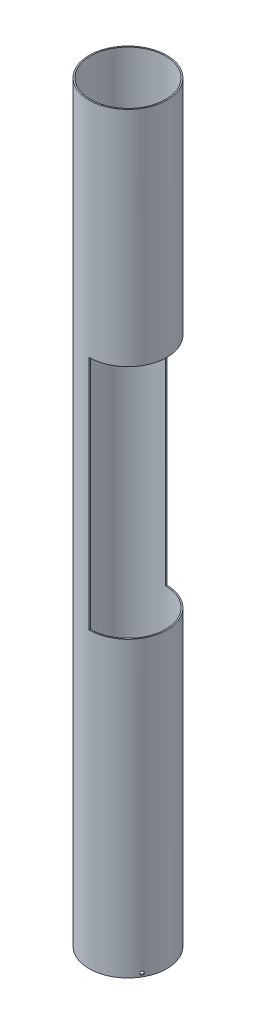
SolidWorks part; units mm, degrees
ref_plane "Front Plane" through (0, 0, 0) normal (0, 0, 1) x (1, 0, 0)
ref_plane "Top Plane" through (0, 0, 0) normal (0, 1, 0) x (1, 0, 0)
ref_plane "Right Plane" through (0, 0, 0) normal (1, 0, 0) x (0, 0, -1)
sketch "Sketch1" plane through (0, 0, 0) normal (0, 1, 0) x (1, 0, 0)
  circle A0 centre (0, 0) radius 38.1
  circle A3 centre (0, 0) radius 39.37
extrude "Boss-Extrude1" add sketch "Sketch1" along normal blind 762
sketch "Sketch2" plane through (0, 0, 0) normal (0, 0, 1) x (1, 0, 0)
  circle A0 centre (0, 3.2871) radius 1.6929
extrude "Cut-Extrude1" cut sketch "Sketch2" against normal blind 61.4
pattern_circular "CirPattern3" count 3 over 360 of "Cut-Extrude1"
sketch "Sketch3" plane through (0, 0, 0) normal (1, 0, 0) x (0, 0, -1)
  line L0 (-39.37, 665.4) -> (-39.37, 0) construction
  line L1 (-39.37, 513.9904) -> (39.37, 513.9904)
  line L2 (-39.37, 513.9904) -> (-39.37, 282.655)
  line L4 (39.37, 513.9904) -> (39.37, 282.655)
  line L5 (39.37, 4.98) -> (39.37, 665.4) construction
  line L6 (-39.37, 282.655) -> (-39.37, 276.305)
  line L7 (-39.37, 665.4) -> (-39.37, 0) construction
  line L8 (-39.37, 276.305) -> (-39.37, 269.955)
  line L10 (39.37, 4.98) -> (39.37, 665.4) construction
  line L11 (39.37, 269.955) -> (39.37, 282.655)
  line L12 (-39.37, 269.955) -> (-39.37, 263.605)
  line L13 (-39.37, 263.605) -> (39.37, 263.605)
  line L14 (39.37, 263.605) -> (39.37, 269.955)
extrude "Cut-Extrude2" [suppressed] cut sketch "Sketch3" along normal blind 72.4
sketch "Sketch4" plane through (0, 0, 0) normal (1, 0, 0) x (0, 0, -1)
  line L1 (-49.7699, 536.3122) -> (47.077, 536.3122)
  line L2 (-49.7699, 536.3122) -> (-49.7699, 297.1597)
  line L3 (-49.7699, 297.1597) -> (47.077, 297.1597)
  line L4 (47.077, 536.3122) -> (47.077, 297.1597)
extrude "Cut-Extrude3" cut sketch "Sketch4" along normal blind 200
